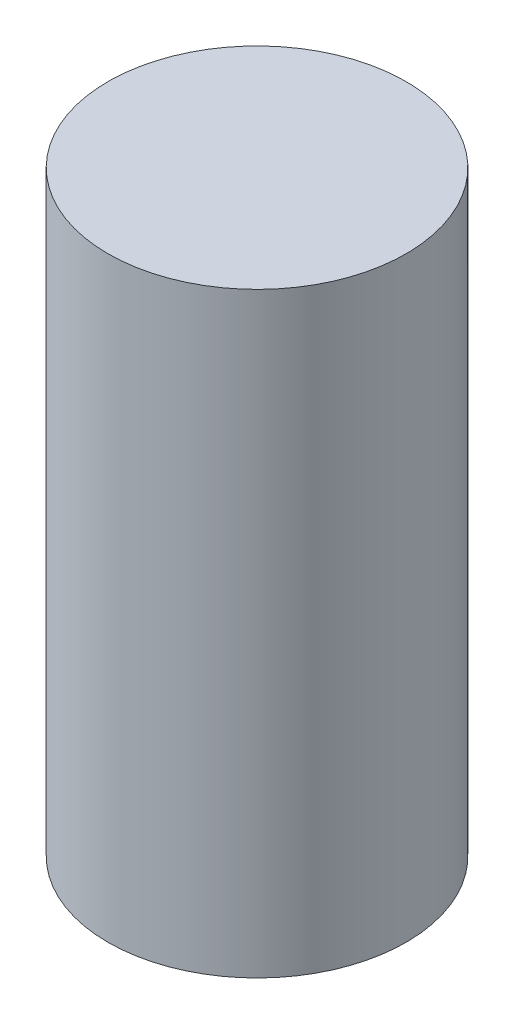
SolidWorks part; units mm, degrees
material "Capacitor"
ref_plane "Front Plane" through (0, 0, 0) normal (0, 0, 1) x (1, 0, 0)
ref_plane "Top Plane" through (0, 0, 0) normal (0, 1, 0) x (1, 0, 0)
ref_plane "Right Plane" through (0, 0, 0) normal (1, 0, 0) x (0, 0, -1)
sketch "Sketch1" plane through (0, 0, 0) normal (0, 1, 0) x (1, 0, 0)
  circle A0 centre (0, 0) radius 2.2225
  dimension "D1" = 4.445
extrude "Boss-Extrude1" add sketch "Sketch1" along normal blind 8.89
